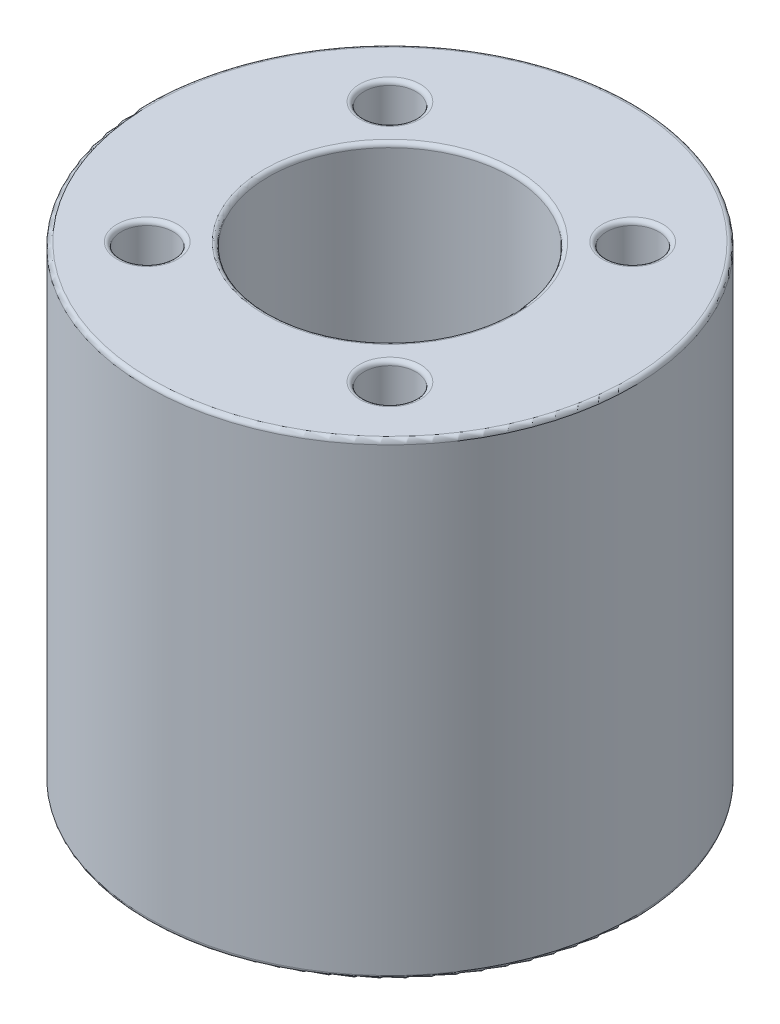
SolidWorks part; units mm, degrees
material "201 Annealed Stainless Steel (SS)"
ref_plane "Front Plane" through (0, 0, 0) normal (0, 0, 1) x (1, 0, 0)
ref_plane "Top Plane" through (0, 0, 0) normal (0, 1, 0) x (1, 0, 0)
ref_plane "Right Plane" through (0, 0, 0) normal (1, 0, 0) x (0, 0, -1)
other "Configuration Table"
sketch "Sketch1" plane through (0, 0, 0) normal (0, 1, 0) x (1, 0, 0)
  circle A0 centre (0, 0) radius 14
  dimension "D1" = 28
extrude "Boss-Extrude1" add sketch "Sketch1" along normal blind 27
sketch "Sketch2" plane through (0, 27, 0) normal (0, 1, 0) x (1, 0, 0)
  circle A0 centre (0, 0) radius 4
  dimension "D1" = 8
extrude "Cut-Extrude1" cut sketch "Sketch2" against normal blind 27
sketch "Sketch3" plane through (0, 27, 0) normal (0, 1, 0) x (1, 0, 0)
  circle A0 centre (0, 0) radius 7
  dimension "D1" = 14
extrude "Cut-Extrude2" cut sketch "Sketch3" against normal blind 12
fillet "Fillet1" radius 0.25 6 edges at (0, 27, 7) (0, 0, 14) (0, 15, 7) (0, 15, 4) (0, 0, 4) (0, 27, 14)
sketch "Sketch4" plane through (0, 27, 0) normal (0, 1, 0) x (1, 0, 0)
  line L1 (7, -7) -> (-7, -7) construction
  line L2 (7, -7) -> (7, 7) construction
  line L3 (7, 7) -> (-7, 7) construction
  line L4 (-7, -7) -> (-7, 7) construction
  line L5 (7, -7) -> (-7, 7) construction
  line L6 (7, 7) -> (-7, -7) construction
  circle A0 centre (-7, 7) radius 1.5
  circle A1 centre (7, 7) radius 1.5
  circle A2 centre (-7, -7) radius 1.5
  circle A3 centre (7, -7) radius 1.5
  point P0 (0, 0)
  dimension "D2" = 3
  dimension "D3" = 3
  dimension "D4" = 3
  dimension "D5" = 3
  dimension "D1" = 14
extrude "Cut-Extrude3" cut sketch "Sketch4" against normal blind 5.5
fillet "Fillet2" radius 0.25 8 edges at (7, 21.5, -5.5) (7, 21.5, 8.5) (-7, 21.5, 8.5) (-7, 21.5, -5.5) (7, 27, -5.5) (7, 27, 8.5) (-7, 27, 8.5) (-7, 27, -5.5)
